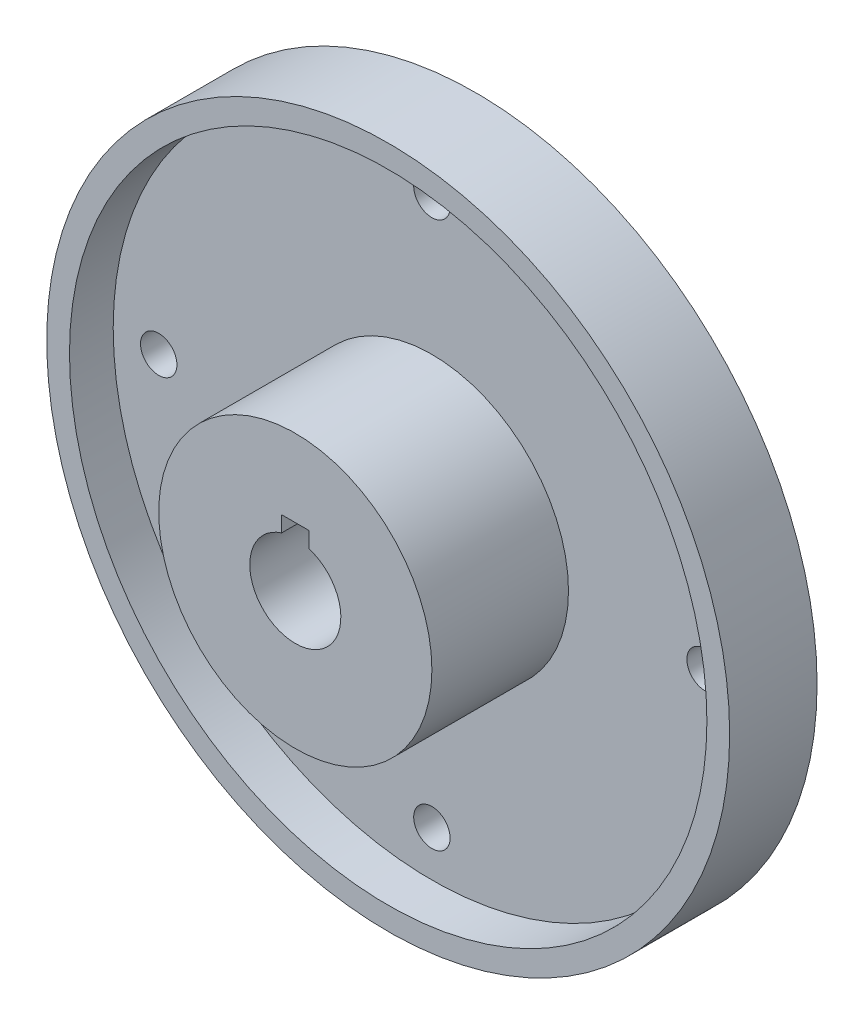
SolidWorks part; units mm, degrees
ref_plane "Front Plane" through (0, 0, 0) normal (0, 0, 1) x (1, 0, 0)
ref_plane "Top Plane" through (0, 0, 0) normal (0, 1, 0) x (1, 0, 0)
ref_plane "Right Plane" through (0, 0, 0) normal (1, 0, 0) x (0, 0, -1)
sketch "Sketch1" plane through (0, 0, 0) normal (0, 0, 1) x (1, 0, 0)
  circle A0 centre (0, 0) radius 75
  dimension "D1" = 150
extrude "Boss-Extrude3" add sketch "Sketch1" along normal blind 19.2
sketch "Sketch3" plane through (0, 0, 19.2) normal (0, 0, 1) x (1, 0, 0)
  circle A0 centre (0, 0) radius 70
  dimension "D1" = 140
extrude "Cut-Extrude1" cut sketch "Sketch3" against normal blind 9.6
sketch "Sketch4" plane through (0, 0, 9.6) normal (0, 0, 1) x (1, 0, 0)
  circle A0 centre (0, 0) radius 30
  dimension "D1" = 60
extrude "Boss-Extrude4" add sketch "Sketch4" along normal blind 30
sketch "Sketch5" plane through (0, 0, 39.6) normal (0, 0, 1) x (1, 0, 0)
  circle A0 centre (0, 0) radius 10
  dimension "D1" = 20
extrude "Cut-Extrude2" cut sketch "Sketch5" against normal blind 57
sketch "Sketch6" plane through (0, 0, 9.6) normal (0, 0, 1) x (1, 0, 0)
  circle A0 centre (0, 60) radius 4
  circle A1 centre (60, 0) radius 4
  circle A2 centre (0, -60) radius 4
  circle A3 centre (-60, 0) radius 4
  dimension "D1" = 8
  dimension "D2" = 60
  dimension "D3" = 4
extrude "Cut-Extrude3" cut sketch "Sketch6" against normal blind 57
sketch "Sketch7" plane through (0, 0, 39.6) normal (0, 0, 1) x (1, 0, 0)
  line L1 (-3, 13) -> (3, 13)
  line L2 (-3, 13) -> (-3, 7)
  line L3 (-3, 7) -> (3, 7)
  line L4 (3, 13) -> (3, 7)
  line L5 (-3, 13) -> (3, 7) construction
  line L6 (-3, 7) -> (3, 13) construction
  circle A0 centre (0, 0) radius 10 construction
  point P0 (0, 10)
  dimension "D1" = 6
  dimension "D2" = 6
extrude "Cut-Extrude4" cut sketch "Sketch7" against normal through all
